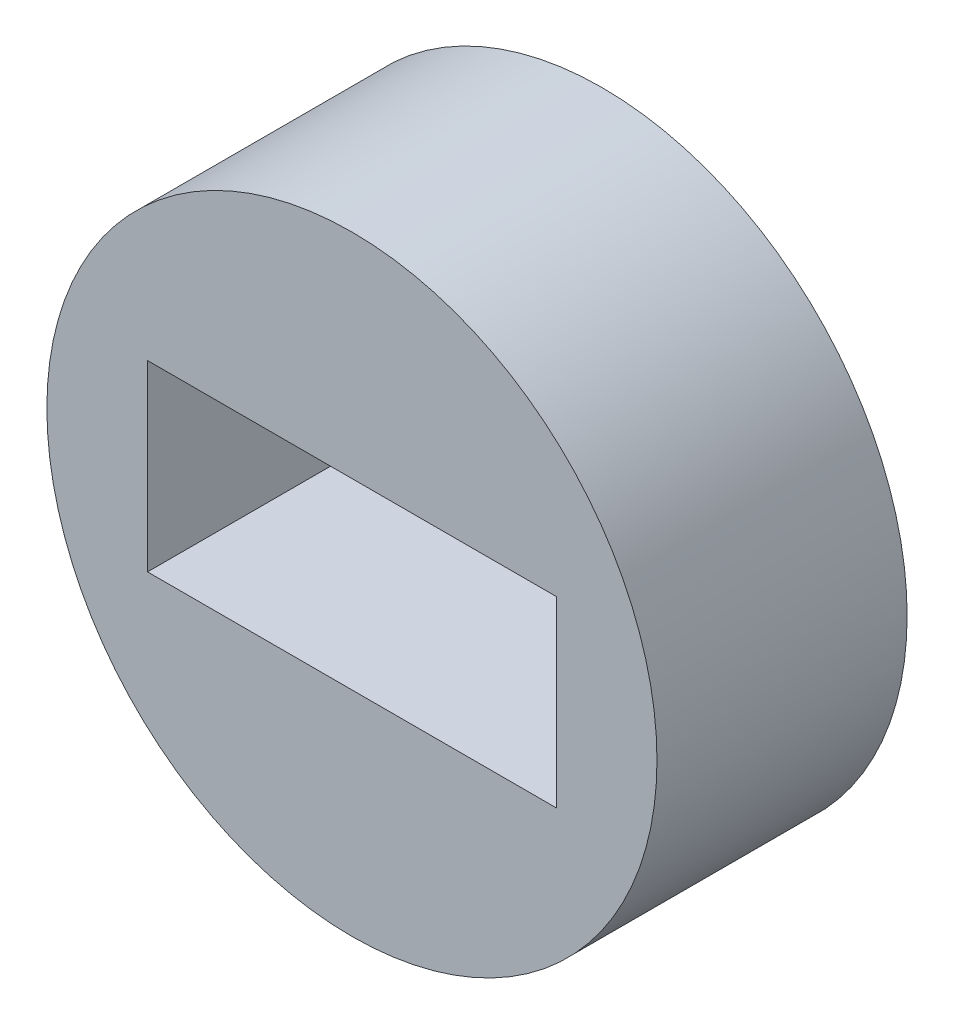
SolidWorks part; units mm, degrees
ref_plane "Front Plane" through (0, 0, 0) normal (0, 0, 1) x (1, 0, 0)
ref_plane "Top Plane" through (0, 0, 0) normal (0, 1, 0) x (1, 0, 0)
ref_plane "Right Plane" through (0, 0, 0) normal (1, 0, 0) x (0, 0, -1)
sketch "Sketch1" plane through (0, 0, 0) normal (0, 0, 1) x (1, 0, 0)
  circle A0 centre (0, 0) radius 50
extrude "Boss-Extrude1" add sketch "Sketch1" along normal blind 41 contours A0
sketch "Sketch2" plane through (0, 0, 41) normal (0, 0, 1) x (1, 0, 0)
  line L1 (-33.5, 15) -> (33.5, 15)
  line L2 (-33.5, 15) -> (-33.5, -15)
  line L3 (-33.5, -15) -> (33.5, -15)
  line L4 (33.5, 15) -> (33.5, -15)
  line L5 (-33.5, 15) -> (33.5, -15) construction
  line L6 (-33.5, -15) -> (33.5, 15) construction
  point P0 (0, 0)
  dimension "D1" = 67
  dimension "D2" = 30
extrude "Cut-Extrude1" cut sketch "Sketch2" against normal blind 41
